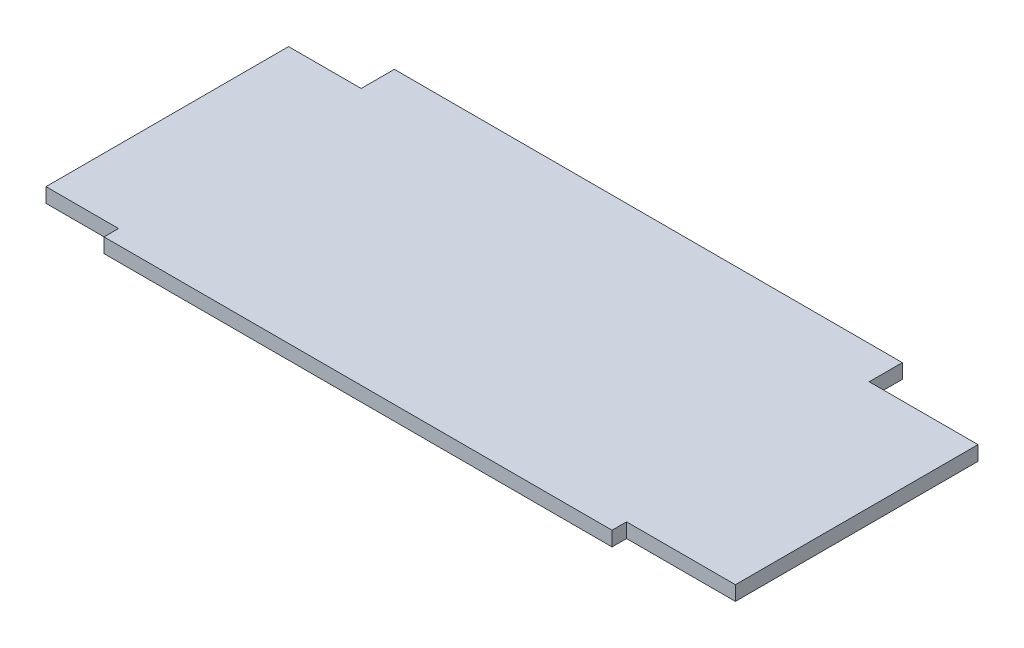
SolidWorks part; units mm, degrees
material "PVC rigido"
ref_plane "Piano frontale" through (0, 0, 0) normal (0, 0, 1) x (1, 0, 0)
ref_plane "Piano superiore" through (0, 0, 0) normal (0, 1, 0) x (1, 0, 0)
ref_plane "Piano destro" through (0, 0, 0) normal (1, 0, 0) x (0, 0, -1)
sketch "Schizzo1" plane through (0, 0, 0) normal (0, 0, 1) x (1, 0, 0)
  line L0 (78, -74.5) -> (148, -74.5) construction
  line L1 (78, -72.5) -> (148, -72.5)
  line L2 (78, -72.5) -> (78, -74.5)
  line L3 (78, -74.5) -> (148, -74.5)
  line L4 (148, -72.5) -> (148, -74.5)
extrude "Estrusione-Estrusione1" add sketch "Schizzo1" along normal up to surface (35.4279 mm away) and the other way up to surface (4.5721 mm away)
sketch "Schizzo2" plane through (148, 0, 0) normal (1, 0, 0) x (0, 0, -1)
  line L0 (-35.4279, -74.5) -> (4.5721, -74.5) construction
  line L1 (0, -72.5) -> (-33.4279, -72.5)
  line L2 (0, -72.5) -> (0, -74.5)
  line L3 (0, -74.5) -> (-33.4279, -74.5)
  line L4 (-33.4279, -72.5) -> (-33.4279, -74.5)
  line L5 (-33.4279, -74.5) -> (-33.4279, -72.5) construction
extrude "Estrusione-Estrusione2" add sketch "Schizzo2" along normal blind 15
sketch "Schizzo3" plane through (78, 0, 0) normal (-1, 0, 0) x (0, 0, 1)
  line L0 (35.4279, -74.5) -> (-4.5721, -74.5) construction
  line L1 (0, -72.5) -> (33.4279, -72.5)
  line L2 (0, -72.5) -> (0, -74.5)
  line L3 (0, -74.5) -> (33.4279, -74.5)
  line L4 (33.4279, -72.5) -> (33.4279, -74.5)
  line L5 (33.4279, -72.5) -> (33.4279, -74.5) construction
extrude "Estrusione-Estrusione3" add sketch "Schizzo3" along normal blind 10
